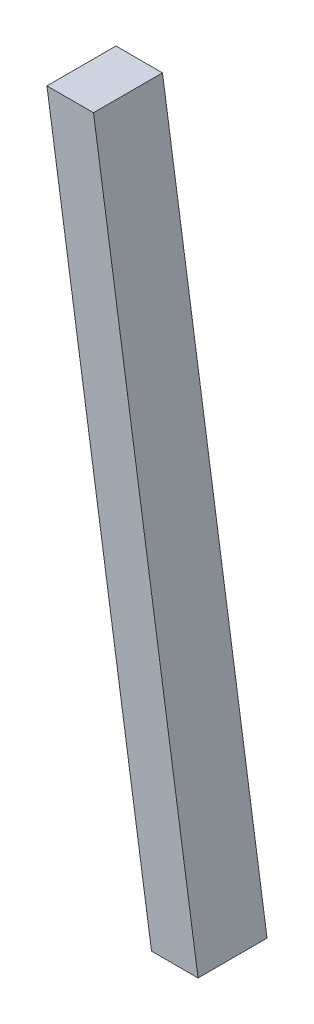
SolidWorks part; units mm, degrees
ref_plane "前基準面" through (0, 0, 0) normal (0, 0, 1) x (1, 0, 0)
ref_plane "上基準面" through (0, 0, 0) normal (0, 1, 0) x (1, 0, 0)
ref_plane "右基準面" through (0, 0, 0) normal (1, 0, 0) x (0, 0, -1)
sketch "草圖1" plane through (0, 0, 0) normal (0, 0, 1) x (1, 0, 0)
  line L0 (0, 0) -> (614.1789, 0) construction
  line L1 (-27.1313, -606) -> (614.1789, -606) construction
  line L2 (0, -40) -> (614.1789, -40) construction
  line L3 (24.2525, 0) -> (115.1525, -606)
  line L4 (64.7, 0) -> (155.6, -606)
  line L5 (24.2525, 0) -> (64.7, 0)
  line L6 (24.2525, 0) -> (44.4763, 0)
  line L7 (115.1525, -606) -> (155.6, -606)
  line L8 (-95, 0) -> (95, -40) construction
  line L9 (95, 0) -> (-95, 0) construction
  line L10 (95, 0) -> (95, -40) construction
  line L11 (95, -40) -> (-95, -40) construction
  line L12 (-95, 0) -> (-95, -40) construction
  line L13 (95, -40) -> (95, 0)
  line L14 (95, 0) -> (-95, -40) construction
  line L15 (0, 0) -> (0, -40) construction
  line L16 (24.2525, 0) -> (30.2525, -40)
  line L17 (42.4325, 0) -> (64.7, 0)
  line L18 (48.4325, -40) -> (42.4325, 0) construction
  line L19 (42.4325, 0) -> (24.2525, 0)
  line L20 (70.7, -40) -> (48.4325, -40) construction
  point P17 (0, -20)
  dimension "D1" = 40
  dimension "D2" = 606
  dimension "D3" = 40
  dimension "D4" = 190
  dimension "D5" = 30.3
  dimension "D6" = 60.6
  dimension "D7" = 18.18
extrude "填料-伸長4" add sketch "草圖1" along normal blind 60 contours L3 L7 L4 L5 L6
